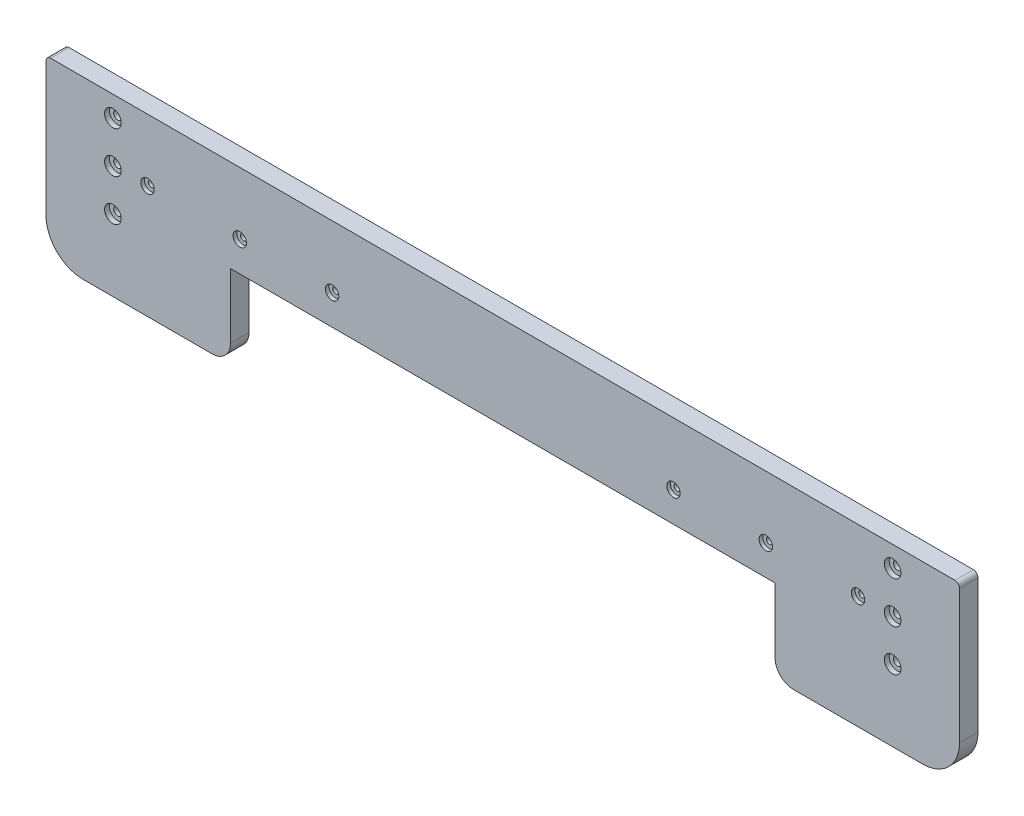
SolidWorks part; units mm, degrees
material "6061 Alloy"
ref_plane "Front Plane" through (0, 0, 0) normal (0, 0, 1) x (1, 0, 0)
ref_plane "Top Plane" through (0, 0, 0) normal (0, 1, 0) x (1, 0, 0)
ref_plane "Right Plane" through (0, 0, 0) normal (1, 0, 0) x (0, 0, -1)
sketch "Sketch1" plane through (0, 0, 0) normal (0, 0, 1) x (1, 0, 0)
  line L0 (-495, 33.1177) -> (-495, 178.1177)
  line L1 (-490, 183.1177) -> (490, 183.1177)
  line L2 (495, 178.1177) -> (495, 33.1177)
  line L3 (455, -6.8823) -> (315, -6.8823)
  line L4 (295, 13.1177) -> (295, 83.1177)
  line L5 (295, 83.1177) -> (-295, 83.1177)
  line L6 (-295, 83.1177) -> (-295, 13.1177)
  line L7 (-315, -6.8823) -> (-455, -6.8823)
  line L8 (0, 183.1177) -> (0, -96.8627) construction
  line L9 (-495, 160.6177) -> (495, 160.6177) construction
  arc A0 (490, 183.1177) -> (495, 178.1177) centre (490, 178.1177) cw
  arc A1 (-495, 178.1177) -> (-490, 183.1177) centre (-490, 178.1177) cw
  arc A2 (315, -6.8823) -> (295, 13.1177) centre (315, 13.1177) cw
  arc A3 (-295, 13.1177) -> (-315, -6.8823) centre (-315, 13.1177) cw
  arc A4 (495, 33.1177) -> (455, -6.8823) centre (455, 33.1177) cw
  arc A5 (-495, 33.1177) -> (-455, -6.8823) centre (-455, 33.1177) ccw
  point P15 (495, 183.1177)
  point P18 (-495, 183.1177)
  point P21 (295, -6.8823)
  point P24 (-295, -6.8823)
  point P27 (495, -6.8823)
  point P30 (-495, -6.8823)
  dimension "D1" = 495
  dimension "D9" = 5
  dimension "D10" = 20
  dimension "D11" = 40
  dimension "D2" = 22.5
  dimension "D3" = 190
  dimension "D4" = 190
  dimension "D5" = 200
  dimension "D6" = 200
  dimension "D7" = 990
  dimension "D8" = 100
extrude "Boss-Extrude1" add sketch "Sketch1" along normal blind 20
hole_wizard "1 Rc Tapped Hole1" positions "Sketch2" profile "Sketch4" size "1" standard "DIN"
sketch "Sketch2" plane through (0, 0, 20) normal (0, 0, 1) x (1, 0, 0)
  point P0 (395.4554, 41.9732)
sketch "Sketch4" plane through (395.4554, 41.9732, 20) normal (1, 0, 0) x (0, -1, 0)
  line L0 (0, 0) -> (0, 20)
  line L1 (0, 20) -> (13.5, 20)
  line L3 (13.5, 20) -> (13.5, 19)
  line L4 (13.5, 19) -> (16.0322, 19)
  line L5 (16.0322, 19) -> (16.6245, 0.025)
  line L6 (16.6245, 0.025) -> (16.6495, 0)
  line L7 (16.6495, 0) -> (0, 0)
  line L8 (0, -6.35) -> (0, 107.95) construction
  line L9 (-16.6245, 0.025) -> (-16.6495, 0) construction
  line L11 (-13.5, 19) -> (-16.0322, 19) construction
  line L12 (-16.0322, 19) -> (-16.6245, 0.025) construction
  dimension "Thru Tap Drill Dia." = 27
  dimension "Thru Tap Drill Depth" = 20
  dimension "Thread Dia." = 33.249
  dimension "Thread Angle" = 3.576
  dimension "Thread Depth" = 19
  dimension "Near C'Sink Dia." = 33.299
  dimension "Near C'Sink Angle" = 90
hole_wizard "CBORE for M8 Hex Head Bolt1" positions "Sketch5" profile "Sketch6" counterbore size "M8" standard "DIN" end condition up to next
sketch "Sketch5" plane through (0, 0, 20) normal (0, 0, 1) x (1, 0, 0)
  line L0 (490, 183.1177) -> (-490, 183.1177) construction
  point P0 (-422.5, 160.6177)
  point P2 (-422.5, 115.6177)
  point P10 (-1342.1281, 1089.9069)
  point P19 (-422.5, 70.6177)
  point P22 (-770.6782, 89.8679)
  dimension "D1" = 422.5
  dimension "D3" = 22.5
  dimension "D4" = 45
  dimension "D5" = 45
sketch "Sketch6" plane through (-422.5, 160.6177, 20) normal (1, 0, 0) x (0, -1, 0)
  line L0 (0, 0) -> (0, 20)
  line L1 (0, 20) -> (4.5, 20)
  line L3 (4.5, 20) -> (4.5, 5.3)
  line L4 (9.0055, 5.3) -> (4.5, 5.3)
  line L5 (9.0055, 5.3) -> (9.0055, 0.025)
  line L6 (9.0055, 0.025) -> (9.0305, 0)
  line L7 (9.0305, 0) -> (0, 0)
  line L8 (-9.0055, 0.025) -> (-9.0305, 0) construction
  line L11 (0, -6.35) -> (0, 107.95) construction
  dimension "Thru Hole Dia." = 9
  dimension "Thru Hole Depth" = 20
  dimension "C'Bore Dia." = 18.011
  dimension "C'Bore Depth" = 5.3
  dimension "Near C'Sink Dia." = 18.061
  dimension "Near C'Sink Angle" = 90
mirror "Mirror1" about plane through (0, 0, 0) normal (1, 0, 0) of "CBORE for M8 Hex Head Bolt1"
hole_wizard "CBORE for M6 Hex Head Bolt1" positions "Sketch7" profile "Sketch8" counterbore size "M6" standard "DIN" end condition up to next
sketch "Sketch7" plane through (0, 0, 20) normal (0, 0, 1) x (1, 0, 0)
  line L0 (0, -11) -> (0, 11) construction
  line L1 (490, 183.1177) -> (-490, 183.1177) construction
  point P0 (-385, 115.6177)
  point P2 (-285, 115.6177)
  point P4 (-185, 115.6177)
  dimension "D1" = 385
  dimension "D2" = 100
  dimension "D3" = 100
  dimension "D4" = 67.5
sketch "Sketch8" plane through (-385, 115.6177, 20) normal (1, 0, 0) x (0, -1, 0)
  line L0 (0, 0) -> (0, 20.001)
  line L1 (0, 20.001) -> (3.3, 20.001)
  line L3 (3.3, 20.001) -> (3.3, 4)
  line L4 (7.2735, 4) -> (3.3, 4)
  line L5 (7.2735, 4) -> (7.2735, 0.025)
  line L6 (7.2735, 0.025) -> (7.2985, 0)
  line L7 (7.2985, 0) -> (0, 0)
  line L8 (-7.2735, 0.025) -> (-7.2985, 0) construction
  line L11 (0, -6.35) -> (0, 107.95) construction
  dimension "Thru Hole Dia." = 6.6
  dimension "Thru Hole Depth" = 20.001
  dimension "C'Bore Dia." = 14.547
  dimension "C'Bore Depth" = 4
  dimension "Near C'Sink Dia." = 14.597
  dimension "Near C'Sink Angle" = 90
mirror "Mirror2" about plane through (0, 0, 0) normal (1, 0, 0) of "CBORE for M6 Hex Head Bolt1"
